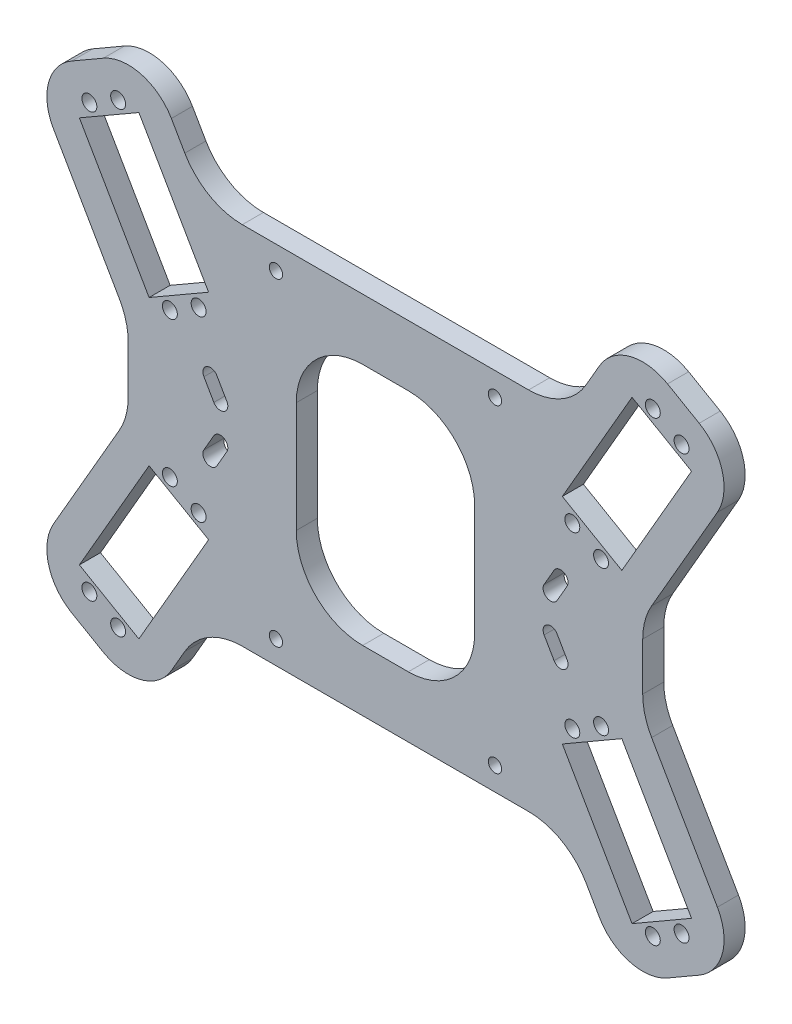
SolidWorks part; units mm, degrees
ref_plane "Plan de face" through (0, 0, 0) normal (0, 0, 1) x (1, 0, 0)
ref_plane "Plan de dessus" through (0, 0, 0) normal (0, 1, 0) x (1, 0, 0)
ref_plane "Plan de droite" through (0, 0, 0) normal (1, 0, 0) x (0, 0, -1)
sketch "Esquisse3" plane through (0, 0, 0) normal (0, 0, 1) x (1, 0, 0)
  line L0 (0, -3.4925) -> (0, 3.4925) construction
  line L1 (-54.6725, 55) -> (54.6725, 55)
  line L2 (-77.5, 12.5385) -> (-77.5, -12.5385)
  line L3 (-54.6725, -55) -> (54.6725, -55)
  line L4 (77.5, 12.5385) -> (77.5, -12.5385)
  line L5 (3.4925, 0) -> (-3.4925, 0) construction
  line L6 (-54.6725, 55) -> (-71.993, 85)
  line L7 (-71.993, 85) -> (-107.5, 64.5)
  line L8 (-107.5, 64.5) -> (-77.5, 12.5385)
  line L9 (-77.5, -12.5385) -> (-107.5, -64.5)
  line L10 (-107.5, -64.5) -> (-71.993, -85)
  line L11 (-71.993, -85) -> (-54.6725, -55)
  line L12 (54.6725, 55) -> (71.993, 85)
  line L13 (71.993, 85) -> (107.5, 64.5)
  line L14 (107.5, 64.5) -> (77.5, 12.5385)
  line L15 (77.5, -12.5385) -> (107.5, -64.5)
  line L16 (107.5, -64.5) -> (71.993, -85)
  line L17 (71.993, -85) -> (54.6725, -55)
  line L19 (-26.875, 36.6667) -> (26.875, 36.6667)
  line L20 (-26.875, 36.6667) -> (-26.875, -36.6667)
  line L21 (-26.875, -36.6667) -> (26.875, -36.6667)
  line L22 (26.875, 36.6667) -> (26.875, -36.6667)
  point P4 (0, 55)
  point P7 (-77.5, 0)
  point P24 (0, -36.6667)
  point P27 (26.875, 0)
  point P28 (0, 0)
  dimension "D3" = 120
  dimension "D6" = 41
  dimension "D7" = 120
  dimension "D8" = 120
  dimension "D9" = 120
  dimension "D2" = 110
  dimension "D10" = 53.75
  dimension "D11" = 73.3333
  dimension "D4" = 170
  dimension "D5" = 215
  dimension "D12" = 60
extrude "Boss.-Extru.2" add sketch "Esquisse3" against normal blind 6.35 separate body
fillet "Congé6" radius 20 12 edges at (77.5, -12.5385, -3.175) (77.5, 12.5385, -3.175) (54.6725, 55, -3.175) (-54.6725, 55, -3.175) (-77.5, 12.5385, -3.175) (-77.5, -12.5385, -3.175) (-54.6725, -55, -3.175) (54.6725, -55, -3.175) (26.875, -36.6667, -3.175) (26.875, 36.6667, -3.175) (-26.875, -36.6667, -3.175) (-26.875, 36.6667, -3.175)
fillet "Congé7" radius 15 8 edges at (71.993, -85, -3.175) (107.5, -64.5, -3.175) (107.5, 64.5, -3.175) (71.993, 85, -3.175) (-71.993, 85, -3.175) (-107.5, 64.5, -3.175) (-71.993, -85, -3.175) (-107.5, -64.5, -3.175)
sketch "Esquisse4" plane through (0, 0, 0) normal (0, 0, 1) x (1, 0, 0)
  line L0 (-53.2831, 32.2936) -> (-74.2831, 68.6667)
  line L1 (-74.2831, 68.6667) -> (-92.2098, 58.3167)
  line L2 (-92.2098, 58.3167) -> (-71.2098, 21.9436)
  line L3 (-71.2098, 21.9436) -> (-53.2831, 32.2936)
  line L4 (-83.2465, 63.4917) -> (-89.7465, 74.75) construction
  line L5 (-84.9833, 77.5) -> (-94.5096, 72) construction
  line L6 (-60.446, 65) -> (-64.493, 72.0096) construction
  line L7 (-49.7465, 5.468) -> (-52.7465, 10.6641) construction
  line L8 (-51.695, 4.343) -> (-54.695, 9.5391)
  line L9 (-47.7979, 6.593) -> (-50.7979, 11.7891)
  line L10 (-56.2914, 26.804) -> (-80.5414, 68.8063) construction
  line L11 (-80.5414, 68.8063) -> (-89.2016, 63.8063) construction
  line L12 (-89.2016, 63.8063) -> (-64.9516, 21.804) construction
  line L13 (-64.9516, 21.804) -> (-56.2914, 26.804) construction
  line L14 (-81.7098, 40.1301) -> (-77.0766, 42.8051) construction
  arc A0 (-51.695, 4.343) -> (-47.7979, 6.593) centre (-49.7465, 5.468) ccw
  arc A1 (-50.7979, 11.7891) -> (-54.695, 9.5391) centre (-52.7465, 10.6641) ccw
  circle A3 centre (-56.2914, 26.804) radius 2.25
  circle A4 centre (-64.9516, 21.804) radius 2.25
  circle A5 centre (-89.2016, 63.8063) radius 2.25
  circle A6 centre (-80.5414, 68.8063) radius 2.25
  point P12 (-51.2465, 8.066)
  point P23 (-84.8715, 66.3063)
  dimension "D5" = 2.25
  dimension "D7" = 48.5
  dimension "D9" = 4.5
  dimension "D1" = 20.7
  dimension "D2" = 42
  dimension "D3" = 13
  dimension "D4" = 19
  dimension "D6" = 6
  dimension "D8" = 10
extrude "Enlèv. mat.-Extru.2" cut sketch "Esquisse4" against normal blind 6.35
mirror "Symétrie1" about plane through (0, 0, 0) normal (0, 1, 0) of "Enlèv. mat.-Extru.2"
mirror "Symétrie2" about plane through (0, 0, 0) normal (1, 0, 0) of "Symétrie1", "Enlèv. mat.-Extru.2"
sketch "Esquisse5" plane through (0, 0, 0) normal (0, 0, 1) x (1, 0, 0)
  line L0 (0, -3.4925) -> (0, 3.4925) construction
  line L1 (-33, 48) -> (33, 48) construction
  line L2 (-33, 48) -> (-33, -48) construction
  line L3 (-33, -48) -> (33, -48) construction
  line L4 (33, 48) -> (33, -48) construction
  line L5 (3.4925, 0) -> (-3.4925, 0) construction
  point P6 (0, 48)
  point P7 (-33, 0)
  point P10 (0, 0)
  dimension "D1" = 66
  dimension "D2" = 96
hole_wizard "Diamètre du perçage Ø4.0 (4)1" positions "Esquisse6" profile "Esquisse7" hole size "Ø4.0" standard "Ansi Metric" end condition through all
sketch "Esquisse6" plane through (0, 0, 0) normal (0, 0, 1) x (1, 0, 0)
  point P0 (33, 48)
  point P3 (-33, 48)
  point P6 (-33, -48)
  point P9 (33, -48)
sketch "Esquisse7" plane through (33, 48, 0) normal (1, 0, 0) x (0, -1, 0)
  line L0 (0, 0) -> (0, 6.35)
  line L1 (0, 6.35) -> (2, 6.35)
  line L2 (2, 6.35) -> (2, 0)
  line L5 (2, 0) -> (0, 0)
  line L11 (0, -6.35) -> (0, 107.95) construction
  dimension "Diamètre du perçage jusqu'au prochain" = 4
  dimension "Profondeur du perçage jusqu'au prochain" = 6.35
equation "\"D10@Esquisse3\"=\"D5@Esquisse3\"/4"
equation "\"D11@Esquisse3\"=\"D2@Esquisse3\"/1.5"
